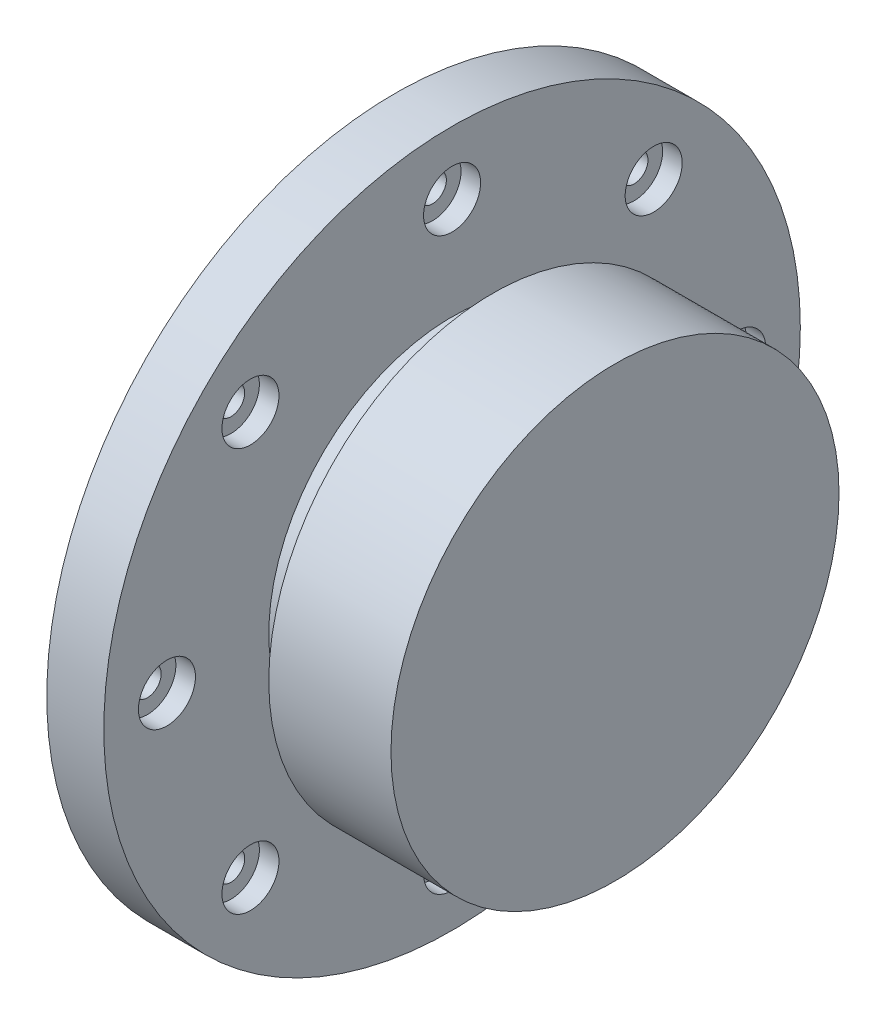
SolidWorks part; units mm, degrees
material "ABS"
ref_plane "Front" through (0, 0, 0) normal (0, 0, 1) x (1, 0, 0)
ref_plane "Top" through (0, 0, 0) normal (0, 1, 0) x (1, 0, 0)
ref_plane "Right" through (0, 0, 0) normal (1, 0, 0) x (0, 0, -1)
sketch "Croquis1" plane through (0, 0, 0) normal (1, 0, 0) x (0, 0, -1)
  circle A0 centre (0, 0) radius 42.75
  dimension "D1" = 85.5
extrude "Saliente-Extruir1" add sketch "Croquis1" along normal mid plane 7
hole_wizard "Refrentado para tornillo con cabeza troncocónica de M31" positions "Croquis2" profile "Croquis3" counterbore size "M3" standard "Ansi Metric"
sketch "Croquis2" plane through (3.5, 0, 0) normal (1, 0, 0) x (0, 0, -1)
  line L0 (0, 16.5) -> (0, -16.5) construction
  line L1 (16.5, 0) -> (-16.5, 0) construction
  point P0 (0, 35)
  point P12 (24.7487, 24.7487)
  point P13 (35, 0)
  point P14 (24.7487, -24.7487)
  point P15 (0, -35)
  point P16 (-24.7487, -24.7487)
  point P18 (-35, 0)
  point P19 (-24.7487, 24.7487)
  dimension "D1" = 35
  dimension "D2" = 8
sketch "Croquis3" plane through (3.5, 35, 0) normal (0, 1, 0) x (0, 0, -1)
  line L0 (0, 0) -> (0, 21.0215)
  line L1 (0, 21.0215) -> (1.7, 20)
  line L2 (1.7, 20) -> (1.7, 2.4)
  line L3 (1.7, 2.4) -> (3.5, 2.4)
  line L4 (3.5, 2.4) -> (3.5, 0)
  line L5 (3.5, 0) -> (0, 0)
  line L10 (0, 21.0215) -> (-1.7, 20) construction
  line L11 (0, -6.35) -> (0, 107.95) construction
  dimension "Diámetro de taladro" = 3.4
  dimension "Profundidad de taladro" = 20
  dimension "Diámetro de refrentado" = 7
  dimension "Profundidad de refrentado" = 2.4
  dimension "Ángulo de perforador" = 118
sketch "Croquis4" plane through (3.5, 0, 0) normal (1, 0, 0) x (0, 0, -1)
  circle A0 centre (0, 0) radius 22.5
  dimension "D1" = 45
extrude "Saliente-Extruir2" add sketch "Croquis4" along normal blind 5
sketch "Croquis5" plane through (8.5, 0, 0) normal (1, 0, 0) x (0, 0, -1)
  circle A0 centre (0, 0) radius 27.5
  dimension "D1" = 55
extrude "Saliente-Extruir3" add sketch "Croquis5" along normal blind 15
